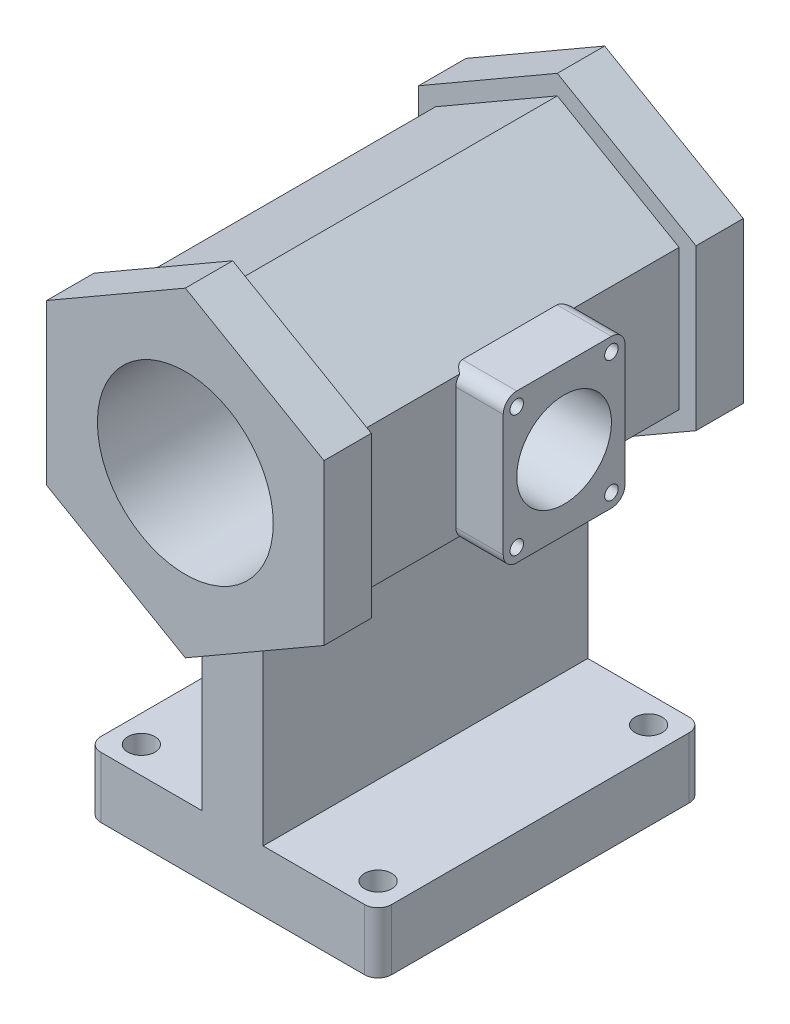
SolidWorks part; units mm, degrees
ref_plane "Спереди" through (0, 0, 0) normal (0, 0, 1) x (1, 0, 0)
ref_plane "Сверху" through (0, 0, 0) normal (0, 1, 0) x (1, 0, 0)
ref_plane "Справа" through (0, 0, 0) normal (1, 0, 0) x (0, 0, -1)
sketch "Эскиз1" plane through (0, 0, 0) normal (0, 0, 1) x (1, 0, 0)
  line L0 (0, 0) -> (0, -505.574) construction
  line L1 (0, 103.923) -> (-90, 51.9615)
  line L2 (-90, 51.9615) -> (-90, -51.9615)
  line L3 (-90, -51.9615) -> (-22.5, -90.9327)
  line L4 (22.5, -90.9327) -> (90, -51.9615)
  line L5 (90, -51.9615) -> (90, 51.9615)
  line L6 (90, 51.9615) -> (0, 103.923)
  line L7 (-107.5, -290) -> (107.5, -290)
  line L8 (107.5, -290) -> (107.5, -245)
  line L9 (107.5, -245) -> (22.5, -245)
  line L10 (22.5, -245) -> (22.5, -90.9327)
  line L11 (-22.5, -245) -> (-22.5, -90.9327)
  line L12 (-107.5, -245) -> (-22.5, -245)
  line L13 (-107.5, -290) -> (-107.5, -245)
  circle A0 centre (0, 0) radius 90 construction
  point P1 (0, -290)
  point P20 (0, -290)
  dimension "D1" = 290
extrude "Бобышка-Вытянуть1" add sketch "Эскиз1" along normal blind 240
sketch "Эскиз2" plane through (0, 0, 240) normal (0, 0, 1) x (1, 0, 0)
  line L1 (0, 118.3568) -> (-102.5, 59.1784)
  line L2 (-102.5, 59.1784) -> (-102.5, -59.1784)
  line L3 (-102.5, -59.1784) -> (0, -118.3568)
  line L4 (0, -118.3568) -> (102.5, -59.1784)
  line L5 (102.5, -59.1784) -> (102.5, 59.1784)
  line L6 (102.5, 59.1784) -> (0, 118.3568)
  circle A0 centre (0, 0) radius 102.5 construction
extrude "Бобышка-Вытянуть2" add sketch "Эскиз2" along normal blind 35
sketch "Эскиз4" plane through (0, 0, 0) normal (0, 0, -1) x (-1, 0, 0)
  line L1 (0, 118.3568) -> (-102.5, 59.1784)
  line L2 (-102.5, 59.1784) -> (-102.5, -59.1784)
  line L3 (-102.5, -59.1784) -> (0, -118.3568)
  line L4 (0, -118.3568) -> (102.5, -59.1784)
  line L5 (102.5, -59.1784) -> (102.5, 59.1784)
  line L6 (102.5, 59.1784) -> (0, 118.3568)
  circle A0 centre (0, 0) radius 102.5 construction
extrude "Бобышка-Вытянуть4" add sketch "Эскиз4" along normal blind 35
sketch "Эскиз5" plane through (90, 0, 0) normal (1, 0, 0) x (0, 0, -1)
  line L0 (0, 0) -> (-240, 0) construction
  line L1 (-240, -59.1784) -> (-240, 59.1784) construction
  line L3 (-75, 55) -> (-165, 55)
  line L4 (-75, 55) -> (-75, -55)
  line L5 (-75, -55) -> (-165, -55)
  line L6 (-165, 55) -> (-165, -55)
  line L7 (-75, 55) -> (-165, -55) construction
  line L8 (-75, -55) -> (-165, 55) construction
  point P5 (-120, 0)
  dimension "D1" = 120
extrude "Бобышка-Вытянуть5" add sketch "Эскиз5" along normal blind 35 and the other way blind 90
sketch "Эскиз6" plane through (0, 0, 275) normal (0, 0, 1) x (1, 0, 0)
  circle A0 centre (0, 0) radius 65
extrude "Вырез-Вытянуть1" cut sketch "Эскиз6" against normal through all
sketch "Эскиз8" plane through (125, 0, 0) normal (1, 0, 0) x (0, 0, -1)
  circle A0 centre (-120, 0) radius 35
extrude "Вырез-Вытянуть2" cut sketch "Эскиз8" against normal up to next
sketch "Эскиз9" plane through (0, -290, 0) normal (0, -1, 0) x (1, 0, 0)
  line L0 (-107.5, 240) -> (-107.5, 0) construction
  line L3 (-102.5, 240) -> (-22.5, 240) construction
  line L4 (102.5, 0) -> (22.5, 0) construction
  line L5 (107.5, 240) -> (107.5, 0) construction
  circle A0 centre (87.5, 220) radius 10
  circle A1 centre (-87.5, 220) radius 10
  circle A2 centre (87.5, 20) radius 10
  circle A3 centre (-87.5, 20) radius 10
  dimension "D1" = 20
  dimension "D2" = 20
  dimension "D3" = 20
  dimension "D4" = 20
extrude "Вырез-Вытянуть3" cut sketch "Эскиз9" against normal up to next
sketch "Эскиз10" plane through (125, 0, 0) normal (1, 0, 0) x (0, 0, -1)
  line L0 (-165, 55) -> (-165, -55) construction
  line L2 (-165, 55) -> (-75, 55) construction
  line L3 (-165, -55) -> (-75, -55) construction
  line L4 (-75, 51.9615) -> (-75, -51.9615) construction
  circle A0 centre (-155, -45) radius 5
  circle A1 centre (-155, 45) radius 5
  circle A2 centre (-85, 45) radius 5
  circle A3 centre (-85, -45) radius 5
  dimension "D1" = 10
  dimension "D2" = 10
  dimension "D3" = 10
  dimension "D4" = 10
extrude "Вырез-Вытянуть4" cut sketch "Эскиз10" against normal blind 30
fillet "Скругление1" radius 10 4 edges at (104.8686, -55, 165) (104.8686, -55, 75) (104.8686, 55, 75) (104.8686, 55, 165)
fillet "Скругление2" radius 10 4 edges at (-107.5, -267.5, 240) (-107.5, -267.5, 0) (107.5, -267.5, 0) (107.5, -267.5, 240)
